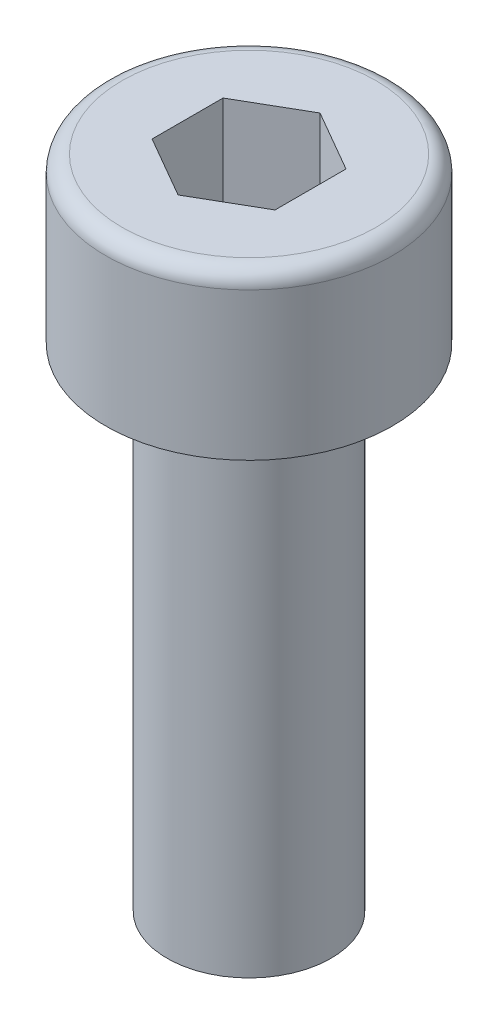
SolidWorks part; units mm, degrees
ref_plane "Front Plane" through (0, 0, 0) normal (0, 0, 1) x (1, 0, 0)
ref_plane "Top Plane" through (0, 0, 0) normal (0, 1, 0) x (1, 0, 0)
ref_plane "Right Plane" through (0, 0, 0) normal (1, 0, 0) x (0, 0, -1)
sketch "Sketch1" plane through (0, 0, 0) normal (0, 0, 1) x (1, 0, 0)
  line L0 (0, 16) -> (-3.1, 16)
  line L1 (-3.5, 15.6) -> (-3.5, 12)
  line L2 (-3.5, 12) -> (-2, 12)
  line L3 (-2, 12) -> (-2, 0)
  line L4 (-2, 0) -> (0, 0)
  line L5 (0, 0) -> (0, 16)
  arc A0 (-3.1, 16) -> (-3.5, 15.6) centre (-3.1, 15.6) ccw
  dimension "D5" = 0.4
  dimension "D1" = 4
  dimension "D2" = 3.5
  dimension "D3" = 12
  dimension "D4" = 2
revolve "Revolve1" add sketch "Sketch1" angle 360 about L5
sketch "Sketch2" plane through (0, 16, 0) normal (0, 1, 0) x (1, 0, 0)
  line L1 (0, 1.7321) -> (-1.5, 0.866)
  line L2 (-1.5, 0.866) -> (-1.5, -0.866)
  line L3 (-1.5, -0.866) -> (0, -1.7321)
  line L4 (0, -1.7321) -> (1.5, -0.866)
  line L5 (1.5, -0.866) -> (1.5, 0.866)
  line L6 (1.5, 0.866) -> (0, 1.7321)
  circle A0 centre (0, 0) radius 1.705
  circle A1 centre (0, 0) radius 1.5 construction
  dimension "D1" = 3.41
  dimension "D2" = 3
extrude "Cut-Extrude1" cut sketch "Sketch2" against normal blind 3 contours L1 L2 L3 L4 L5 L6
